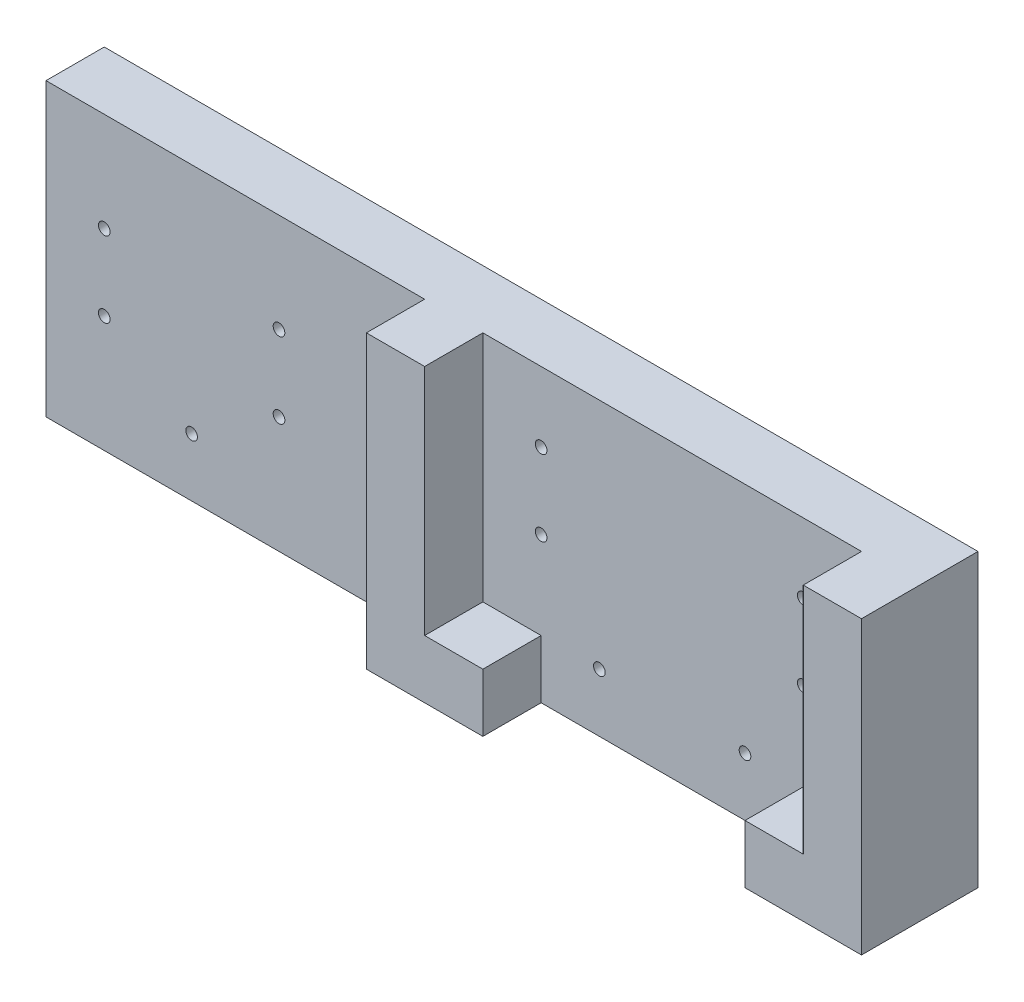
SolidWorks part; units mm, degrees
ref_plane "Plan de face" through (0, 0, 0) normal (0, 0, 1) x (1, 0, 0)
ref_plane "Plan de dessus" through (0, 0, 0) normal (0, 1, 0) x (1, 0, 0)
ref_plane "Plan de droite" through (0, 0, 0) normal (1, 0, 0) x (0, 0, -1)
sketch "Esquisse1" plane through (0, 0, -20) normal (0, 0, -1) x (-1, 0, 0)
  line L0 (-63.8586, 59.5358) -> (-63.8586, 9.5358)
  line L1 (-63.8586, 59.5358) -> (86.1414, 59.5358)
  line L2 (-63.8586, 9.5358) -> (86.1414, 9.5358)
  line L3 (86.1414, 59.5358) -> (86.1414, 9.5358)
  line L4 (-53.8586, 59.5358) -> (11.1414, 59.5358) construction
  line L5 (-53.8586, 19.5358) -> (-53.8586, 59.5358) construction
  line L6 (-43.8586, 19.5358) -> (-53.8586, 19.5358) construction
  circle A0 centre (-43.8586, 47.5358) radius 1
  circle A1 centre (-43.8586, 34.5358) radius 1
  circle A2 centre (1.1414, 34.5358) radius 1
  circle A3 centre (1.1414, 47.5358) radius 1
  circle A4 centre (-8.8586, 19.5358) radius 1
  circle A5 centre (-33.8586, 19.5358) radius 1
  circle A6 centre (76.1414, 29.5358) radius 1
  circle A7 centre (76.1414, 42.5358) radius 1
  circle A8 centre (46.1414, 42.5358) radius 1
  circle A9 centre (46.1414, 29.5358) radius 1
  circle A10 centre (61.1414, 19.5358) radius 1
  dimension "D4" = 2
  dimension "D5" = 2
  dimension "D6" = 2
  dimension "D7" = 2
  dimension "D8" = 2
  dimension "D9" = 2
  dimension "D10" = 2
  dimension "D11" = 2
  dimension "D12" = 2
  dimension "D13" = 2
  dimension "D14" = 2
  dimension "D1" = 150
  dimension "D2" = 10
  dimension "D3" = 10
extrude "Boss.-Extru.1" add sketch "Esquisse1" along normal blind 10
sketch "Esquisse2" plane through (0, 0, -20) normal (0, 0, 1) x (1, 0, 0)
  line L0 (-21.1414, 9.5358) -> (-21.1414, 59.5358)
  line L1 (-21.1414, 9.5358) -> (-1.1414, 9.5358)
  line L2 (-21.1414, 59.5358) -> (-1.1414, 59.5358)
  line L3 (-1.1414, 9.5358) -> (-1.1414, 59.5358)
  line L4 (63.8586, 9.5358) -> (-86.1414, 9.5358) construction
  line L5 (-86.1414, 59.5358) -> (63.8586, 59.5358) construction
  line L6 (-1.1414, 19.5358) -> (-1.1414, -100.4642) construction
  line L7 (-11.1414, 19.5358) -> (-1.1414, 19.5358)
  line L8 (-11.1414, 19.5358) -> (-11.1414, 59.5358)
  line L9 (-1.1414, 19.5358) -> (-1.1414, 59.5358)
  line L10 (-11.1414, 59.5358) -> (-1.1414, 59.5358)
  line L11 (63.8586, 9.5358) -> (43.8586, 9.5358)
  line L12 (63.8586, 9.5358) -> (63.8586, 59.5358)
  line L13 (43.8586, 9.5358) -> (43.8586, 59.5358)
  line L14 (63.8586, 59.5358) -> (43.8586, 59.5358)
  line L15 (43.8586, 19.5358) -> (43.8586, -100.4642) construction
  line L16 (43.8586, 19.5358) -> (53.8586, 19.5358)
  line L17 (43.8586, 19.5358) -> (43.8586, 59.5358)
  line L18 (53.8586, 19.5358) -> (53.8586, 59.5358)
  line L19 (43.8586, 59.5358) -> (53.8586, 59.5358)
  point P22 (-11.1414, 39.5358)
  line M7 (63.8586, 59.5358) -> (-86.1414, 59.5358)
  line M9 (-86.1414, 9.5358) -> (63.8586, 9.5358)
  line M10 (63.8586, 9.5358) -> (63.8586, 59.5358)
  dimension "D1" = 10
extrude "Boss.-Extru.2" add sketch "Esquisse2" along normal blind 10 contours L7 L8 L2 L0 L3 M9 | L18 L16 L13 M9 M10 M7
